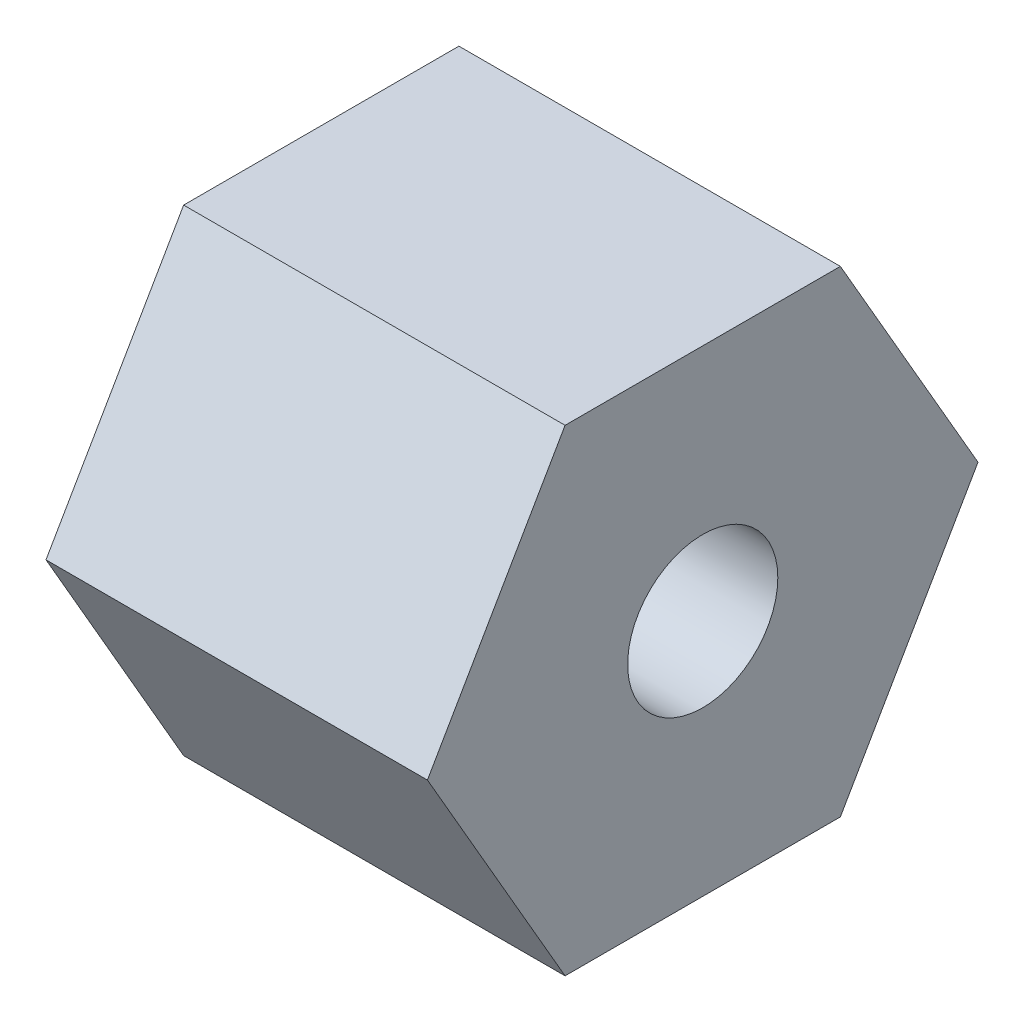
SolidWorks part; units mm, degrees
ref_plane "Front Plane" through (0, 0, 0) normal (0, 0, 1) x (1, 0, 0)
ref_plane "Top Plane" through (0, 0, 0) normal (0, 1, 0) x (1, 0, 0)
ref_plane "Right Plane" through (0, 0, 0) normal (1, 0, 0) x (0, 0, -1)
sketch "Sketch2" plane through (0, 0, 0) normal (1, 0, 0) x (0, 0, -1)
  line L1 (7.3323, 0) -> (3.6662, 6.35)
  line L2 (3.6662, 6.35) -> (-3.6662, 6.35)
  line L3 (-3.6662, 6.35) -> (-7.3323, 0)
  line L4 (-7.3323, 0) -> (-3.6662, -6.35)
  line L5 (-3.6662, -6.35) -> (3.6662, -6.35)
  line L6 (3.6662, -6.35) -> (7.3323, 0)
  circle A0 centre (0, 0) radius 6.35 construction
  circle A1 centre (0, 0) radius 2
  dimension "D1" = 12.7
  dimension "D2" = 4
extrude "Boss-Extrude1" add sketch "Sketch2" along normal mid plane 10.16
